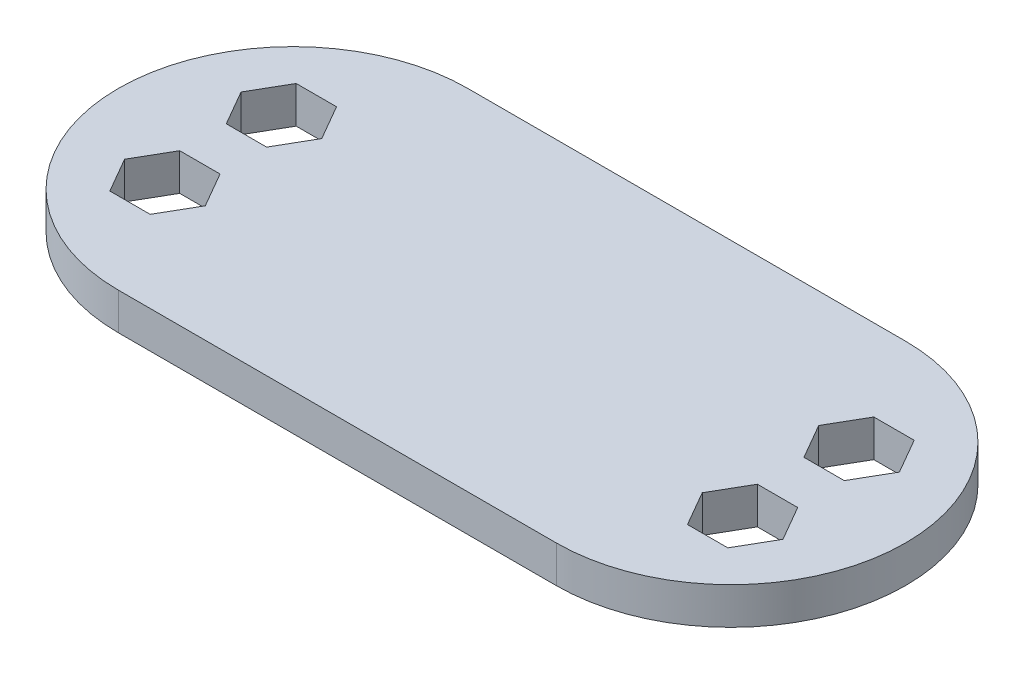
SolidWorks part; units mm, degrees
ref_plane "Front Plane" through (0, 0, 0) normal (0, 0, 1) x (1, 0, 0)
ref_plane "Top Plane" through (0, 0, 0) normal (0, 1, 0) x (1, 0, 0)
ref_plane "Right Plane" through (0, 0, 0) normal (1, 0, 0) x (0, 0, -1)
sketch "Sketch2" plane through (0, 0, 0) normal (0, 1, 0) x (1, 0, 0)
  line L0 (-145.5214, 0.9971) -> (-107.9214, 0.9971)
  line L2 (-145.5214, -29.0029) -> (-107.9214, -29.0029)
  line L4 (-151.5214, 3.0634) -> (-151.5214, -29.2944) construction
  line L9 (-101.9214, 1.8989) -> (-101.9214, -30.7894) construction
  line L10 (-126.7214, 0.9971) -> (-126.7214, -29.0029) construction
  line L11 (-149.7894, -12.0029) -> (-148.0573, -9.0029)
  line L12 (-148.0573, -9.0029) -> (-149.7894, -6.0029)
  line L13 (-149.7894, -6.0029) -> (-153.2535, -6.0029)
  line L14 (-153.2535, -6.0029) -> (-154.9855, -9.0029)
  line L15 (-154.9855, -9.0029) -> (-153.2535, -12.0029)
  line L16 (-153.2535, -12.0029) -> (-149.7894, -12.0029)
  line L17 (-160.5214, -14.0029) -> (-126.7214, -14.0029) construction
  line L18 (-153.2535, -16.0029) -> (-149.7894, -16.0029)
  line L19 (-154.9855, -19.0029) -> (-153.2535, -16.0029)
  line L20 (-153.2535, -22.0029) -> (-154.9855, -19.0029)
  line L21 (-149.7894, -22.0029) -> (-153.2535, -22.0029)
  line L22 (-148.0573, -19.0029) -> (-149.7894, -22.0029)
  line L23 (-149.7894, -16.0029) -> (-148.0573, -19.0029)
  line L24 (-103.6535, -16.0029) -> (-105.3855, -19.0029)
  line L25 (-105.3855, -19.0029) -> (-103.6535, -22.0029)
  line L26 (-103.6535, -22.0029) -> (-100.1894, -22.0029)
  line L27 (-100.1894, -22.0029) -> (-98.4573, -19.0029)
  line L28 (-98.4573, -19.0029) -> (-100.1894, -16.0029)
  line L29 (-100.1894, -16.0029) -> (-103.6535, -16.0029)
  line L30 (-100.1894, -12.0029) -> (-103.6535, -12.0029)
  line L31 (-98.4573, -9.0029) -> (-100.1894, -12.0029)
  line L32 (-100.1894, -6.0029) -> (-98.4573, -9.0029)
  line L33 (-103.6535, -6.0029) -> (-100.1894, -6.0029)
  line L34 (-105.3855, -9.0029) -> (-103.6535, -6.0029)
  line L35 (-103.6535, -12.0029) -> (-105.3855, -9.0029)
  arc A0 (-145.5214, 0.9971) -> (-145.5214, -29.0029) centre (-145.5214, -14.0029) ccw
  arc A7 (-107.9214, -29.0029) -> (-107.9214, 0.9971) centre (-107.9214, -14.0029) ccw
  circle A8 centre (-151.5214, -9.0029) radius 3 construction
  circle A9 centre (-151.5214, -19.0029) radius 3 construction
  circle A10 centre (-101.9214, -19.0029) radius 3 construction
  circle A11 centre (-101.9214, -9.0029) radius 3 construction
  dimension "D5" = 24.8
  dimension "D4" = 6
  dimension "D1" = 30
  dimension "D2" = 6
  dimension "D3" = 5
  dimension "D9" = 6
  dimension "D10" = 0
extrude "Boss-Extrude1" add sketch "Sketch2" along normal blind 3.175
